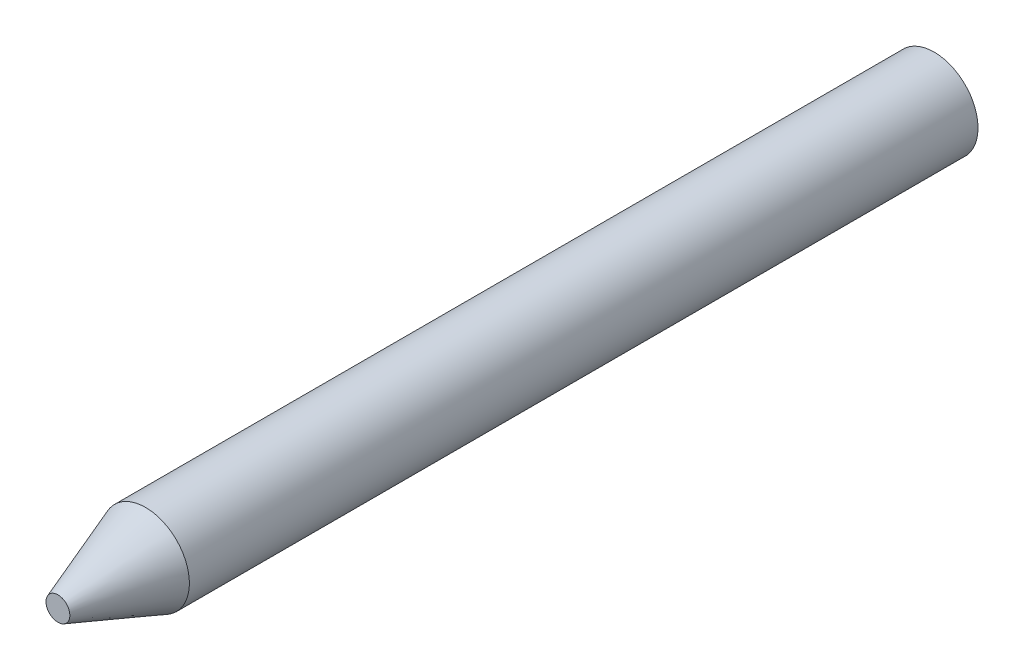
SolidWorks part; units mm, degrees
ref_plane "Спереди" through (0, 0, 0) normal (0, 0, 1) x (1, 0, 0)
ref_plane "Сверху" through (0, 0, 0) normal (0, 1, 0) x (1, 0, 0)
ref_plane "Справа" through (0, 0, 0) normal (1, 0, 0) x (0, 0, -1)
sketch "Эскиз1" plane through (0, 0, 0) normal (0, 0, 1) x (1, 0, 0)
  circle A0 centre (0, 0) radius 3.5
  dimension "D1" = 7
extrude "Бобышка-Вытянуть1" add sketch "Эскиз1" along normal blind 70
chamfer "Фаска1" distance 7 angle 20 1 edges at (3.5, 0, 70)
